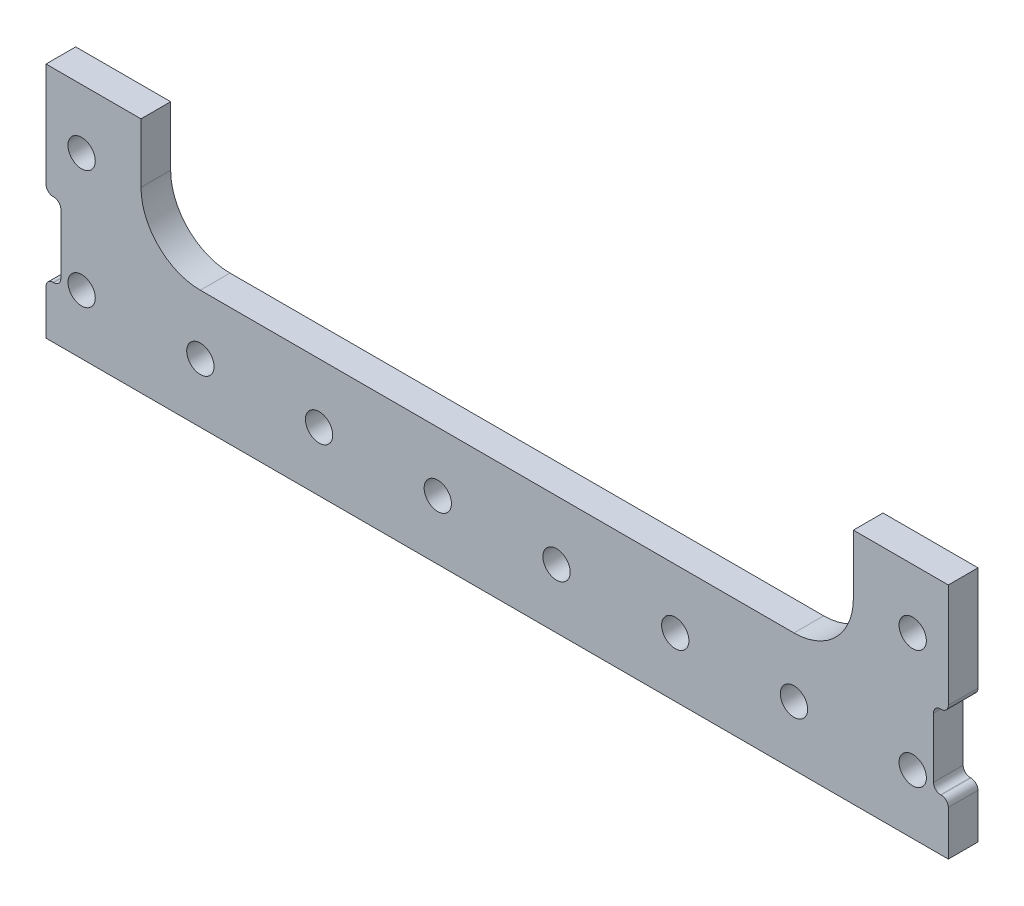
SolidWorks part; units mm, degrees
ref_plane "Front Plane" through (0, 0, 0) normal (0, 0, 1) x (1, 0, 0)
ref_plane "Top Plane" through (0, 0, 0) normal (0, 1, 0) x (1, 0, 0)
ref_plane "Right Plane" through (0, 0, 0) normal (1, 0, 0) x (0, 0, -1)
sketch "Sketch1" plane through (0, 0, 0) normal (0, 0, 1) x (1, 0, 0)
  line L0 (0, 0) -> (0, 50.8)
  line L1 (0, 50.8) -> (25.4, 50.8)
  line L2 (25.4, 50.8) -> (25.4, 25.4)
  line L5 (203.2, 0) -> (0, 0)
  line L6 (25.4, 25.4) -> (177.8, 25.4)
  line L7 (177.8, 25.4) -> (177.8, 50.8)
  line L8 (177.8, 50.8) -> (203.2, 50.8)
  line L9 (203.2, 50.8) -> (203.2, 0)
  dimension "D1" = 50.8
  dimension "D2" = 25.4
  dimension "D3" = 25.4
  dimension "3" = 203.2
extrude "Boss-Extrude1" add sketch "Sketch1" along normal blind 6.35
sketch "Sketch2" plane through (0, 0, 6.35) normal (0, 0, 1) x (1, 0, 0)
  line L0 (25.4, 50.8) -> (0, 50.8) construction
  line L1 (25.4, 25.4) -> (25.4, 50.8) construction
  line L2 (0, 0) -> (203.2, 0) construction
  line L3 (101.6, 25.4) -> (101.6, 0) construction
  line L6 (177.8, 25.4) -> (25.4, 25.4) construction
  line L7 (0, 0) -> (203.2, 0) construction
  circle A0 centre (12.7, 38.1) radius 2.921
  circle A1 centre (12.7, 12.7) radius 2.921
  circle A11 centre (38.1, 12.7) radius 2.921
  circle A12 centre (63.5, 12.7) radius 2.921
  circle A13 centre (88.9, 12.7) radius 2.921
  circle A14 centre (114.3, 12.7) radius 2.921
  circle A15 centre (139.7, 12.7) radius 2.921
  circle A16 centre (165.1, 12.7) radius 2.921
  circle A17 centre (190.5, 12.7) radius 2.921
  circle A19 centre (190.5, 38.1) radius 2.921
  dimension "D1" = 5.842
  dimension "D2" = 12.7
  dimension "D3" = 12.7
  dimension "D4" = 12.7
  dimension "D5" = 8
extrude "Cut-Extrude1" cut sketch "Sketch2" against normal through all
sketch "Sketch3" plane through (0, 0, 6.35) normal (0, 0, 1) x (1, 0, 0)
  line L0 (101.6, 25.4) -> (101.6, 0) construction
  line L1 (0, 0) -> (5.08, 0)
  line L2 (0, 0) -> (0, 50.8)
  line L3 (0, 50.8) -> (5.08, 50.8)
  line L4 (5.08, 0) -> (5.08, 50.8)
  line L5 (177.8, 25.4) -> (25.4, 25.4) construction
  line L6 (0, 0) -> (203.2, 0) construction
  line L7 (198.12, 0) -> (198.12, 50.8)
  line L8 (203.2, 50.8) -> (198.12, 50.8)
  line L9 (203.2, 0) -> (203.2, 50.8)
  line L10 (203.2, 0) -> (198.12, 0)
  line L11 (25.4, 50.8) -> (0, 50.8) construction
  dimension "D1" = 5.08
extrude "Cut-Extrude2" cut sketch "Sketch3" against normal through all
fillet "Fillet1" radius 12.7 2 edges at (177.8, 25.4, 3.175) (25.4, 25.4, 3.175)
sketch "Sketch4" plane through (0, 0, 6.35) normal (0, 0, 1) x (1, 0, 0)
  line L0 (5.08, 0) -> (5.08, 50.8) construction
  line L1 (5.08, 11.1125) -> (8.255, 11.1125)
  line L2 (5.08, 11.1125) -> (5.08, 26.9875)
  line L3 (5.08, 26.9875) -> (8.255, 26.9875)
  line L4 (8.255, 11.1125) -> (8.255, 26.9875)
  line L5 (101.6, 25.4) -> (101.6, 0) construction
  line L6 (165.1, 25.4) -> (38.1, 25.4) construction
  line L7 (5.08, 0) -> (198.12, 0) construction
  line L8 (25.4, 50.8) -> (5.08, 50.8) construction
  line L9 (194.945, 11.1125) -> (194.945, 26.9875)
  line L10 (198.12, 26.9875) -> (194.945, 26.9875)
  line L11 (198.12, 11.1125) -> (198.12, 26.9875)
  line L12 (198.12, 11.1125) -> (194.945, 11.1125)
  dimension "D1" = 15.875
  dimension "D2" = 23.8125
  dimension "D3" = 3.175
extrude "Cut-Extrude3" cut sketch "Sketch4" against normal through all
fillet "Fillet2" radius 1.524 8 edges at (194.945, 11.1125, 3.175) (198.12, 11.1125, 3.175) (194.945, 26.9875, 3.175) (198.12, 26.9875, 3.175) (8.255, 11.1125, 3.175) (5.08, 11.1125, 3.175) (8.255, 26.9875, 3.175) (5.08, 26.9875, 3.175)
